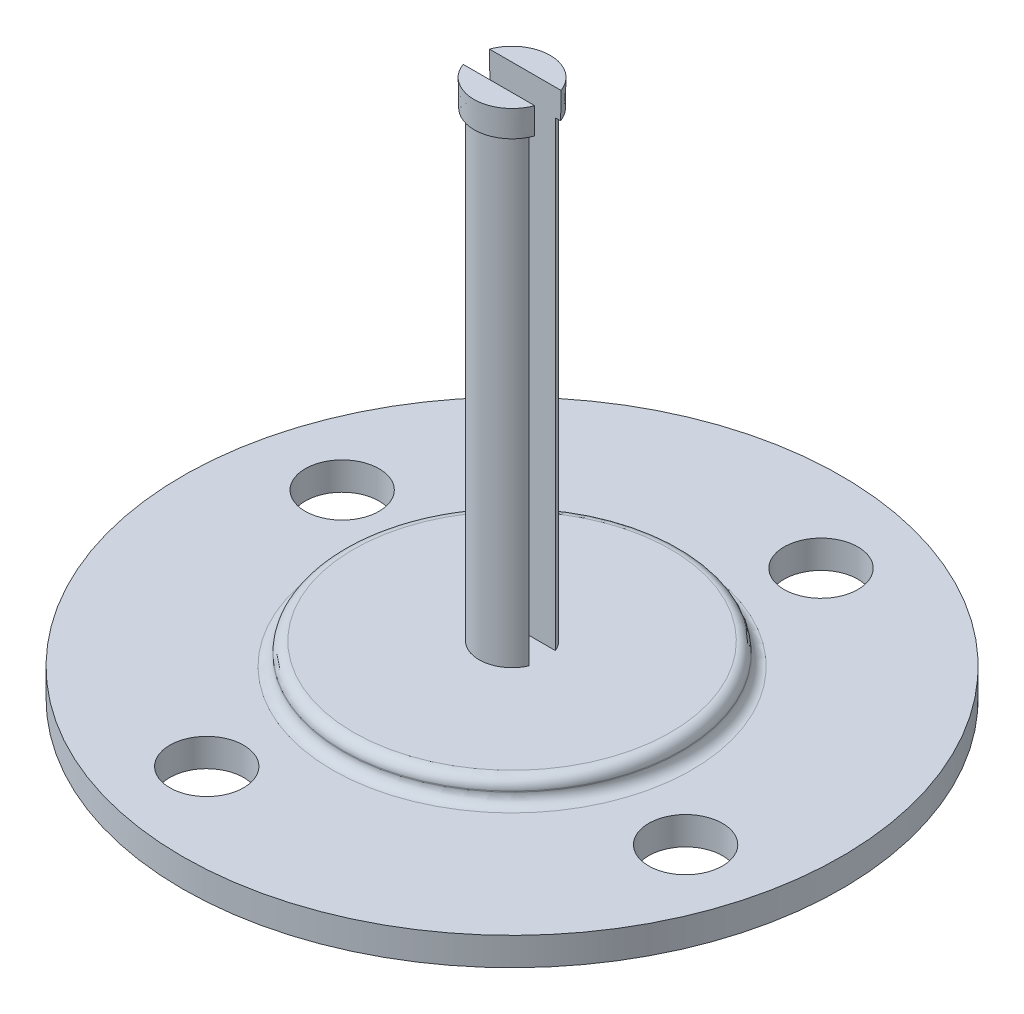
SolidWorks part; units mm, degrees
ref_plane "Front Plane" through (0, 0, 0) normal (0, 0, 1) x (1, 0, 0)
ref_plane "Top Plane" through (0, 0, 0) normal (0, 1, 0) x (1, 0, 0)
ref_plane "Right Plane" through (0, 0, 0) normal (1, 0, 0) x (0, 0, -1)
sketch "Sketch1" plane through (0, 0, 0) normal (0, 0, 1) x (1, 0, 0)
  line L0 (-0.1728, 49.6391) -> (-0.1728, 0.012)
  line L1 (-0.1728, -2.1943) -> (31.5772, -2.1943)
  line L2 (-0.1728, -2.1943) -> (-0.1728, 0.012)
  line L3 (3.0022, 2.6314) -> (16.1214, 2.6314)
  line L4 (16.1214, 2.6314) -> (16.1214, 0.5068)
  line L5 (16.1214, 0.5068) -> (31.5772, 0.5068)
  line L6 (-0.1728, 0.012) -> (31.5772, -2.1943) construction
  line L7 (-0.1728, 49.6391) -> (3.5031, 49.6391)
  line L8 (31.5772, 0.5068) -> (31.5772, -2.1943)
  line L9 (3.4647, 47.0814) -> (3.0022, 47.0814)
  line L10 (3.0022, 47.0814) -> (3.0022, 2.6314)
  line L11 (3.5031, 49.6391) -> (3.4647, 47.0814)
  point P0 (0, 0)
  dimension "D2" = 31.75
  dimension "D3" = 44.45
  dimension "D4" = 3.175
revolve "Revolve1" add sketch "Sketch1" angle 360 about L0
fillet "Fillet1" radius 1.016 2 edges at (-0.1728, 0.5068, 16.2942) (-0.1728, 2.6314, 16.2942)
sketch "Sketch5" plane through (0, 0.5068, 0) normal (0, 1, 0) x (1, 0, 0)
  circle A0 centre (-23.0649, 6.5228) radius 3.556
  circle A1 centre (6.5228, 23.0649) radius 3.556
  circle A2 centre (23.0649, -6.5228) radius 3.556
  circle A3 centre (-6.5228, -23.0649) radius 3.556
  point P11 (0, 0)
  dimension "D1" = 4
extrude "Cut-Extrude4" cut sketch "Sketch5" against normal up to surface (2.7011 mm away) up to face at (-0.1728, -2.1943, 31.75)
sketch "Sketch9" plane through (0, 0, 0) normal (0, 0, 1) x (1, 0, 0)
  line L0 (3.0022, 2.6314) -> (-3.3478, 2.6314) construction
  line L1 (-70.1388, 131.4223) -> (35.4313, 131.4223)
  line L2 (-70.1388, 131.4223) -> (-70.1388, 2.6314)
  line L3 (-70.1388, 2.6314) -> (35.4313, 2.6314)
  line L4 (35.4313, 131.4223) -> (35.4313, 2.6314)
  line L5 (-70.1388, 131.4223) -> (35.4313, 2.6314) construction
  line L6 (-70.1388, 2.6314) -> (35.4313, 131.4223) construction
  point P0 (-17.3538, 67.0268)
extrude "Cut-Extrude5" cut sketch "Sketch9" against normal mid plane 2.54
